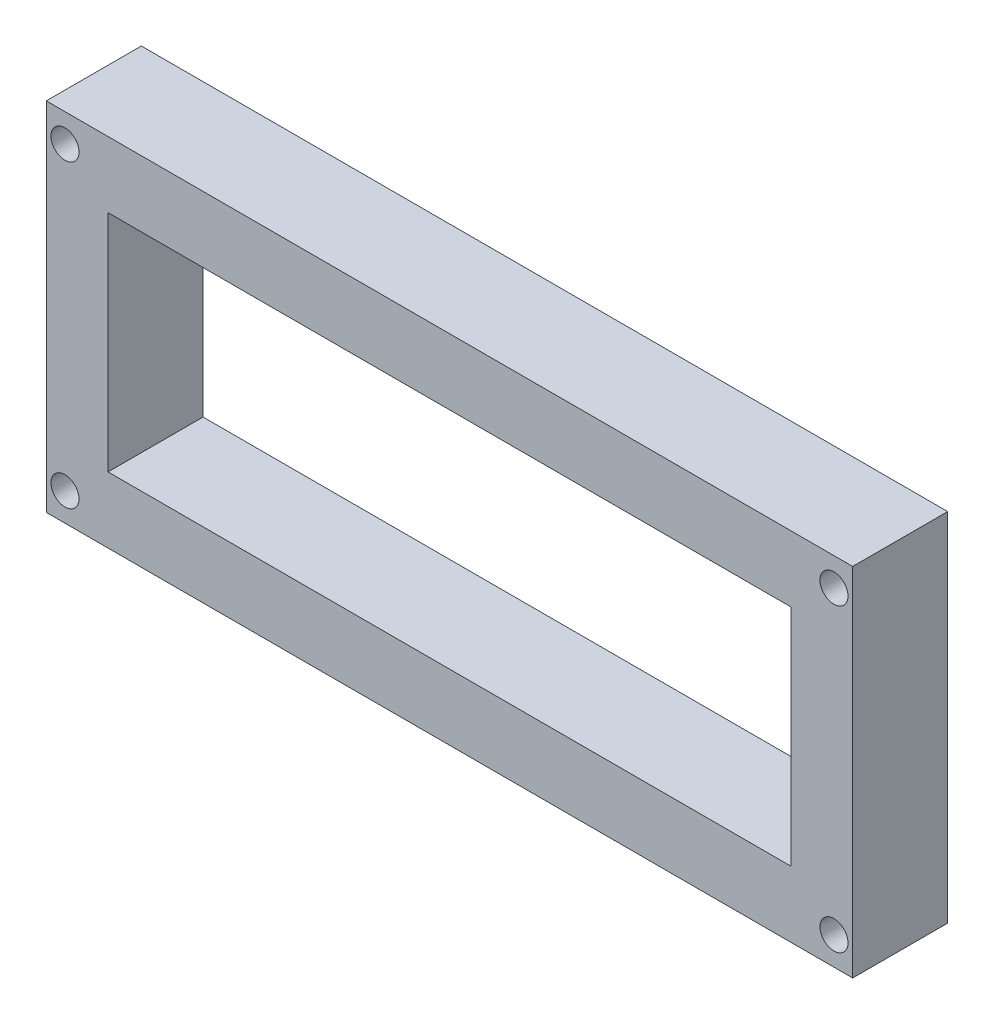
SolidWorks part; units mm, degrees
ref_plane "Front Plane" through (0, 0, 0) normal (0, 0, 1) x (1, 0, 0)
ref_plane "Top Plane" through (0, 0, 0) normal (0, 1, 0) x (1, 0, 0)
ref_plane "Right Plane" through (0, 0, 0) normal (1, 0, 0) x (0, 0, -1)
sketch "Sketch1" plane through (0, 0, 0) normal (0, 0, 1) x (1, 0, 0)
  line L1 (-43.1, 19.05) -> (43.1, 19.05)
  line L2 (-43.1, 19.05) -> (-43.1, -19.05)
  line L3 (-43.1, -19.05) -> (43.1, -19.05)
  line L4 (43.1, 19.05) -> (43.1, -19.05)
  line L5 (-36.5, 12) -> (36.5, 12)
  line L6 (-36.5, 12) -> (-36.5, -12)
  line L7 (-36.5, -12) -> (36.5, -12)
  line L8 (36.5, 12) -> (36.5, -12)
  point P4 (0, 19.05)
  point P5 (-43.1, 0)
  point P11 (0, 12)
  point P12 (-36.5, 0)
  dimension "D1" = 86.2
  dimension "D2" = 38.1
  dimension "D3" = 73
  dimension "D4" = 24
extrude "Boss-Extrude1" add sketch "Sketch1" along normal blind 10.16
sketch "Sketch2" plane through (0, 0, 10.16) normal (0, 0, 1) x (1, 0, 0)
  line L0 (43.1, -19.05) -> (43.1, 19.05) construction
  line L1 (43.1, 19.05) -> (-43.1, 19.05) construction
  line L2 (0, -5.588) -> (0, 5.588) construction
  line L4 (5.588, 0) -> (-5.588, 0) construction
  circle A1 centre (41.1, 16.05) radius 1.5
  circle A2 centre (-41.1, 16.05) radius 1.5
  circle A3 centre (-41.1, -16.05) radius 1.5
  circle A4 centre (41.1, -16.05) radius 1.5
  dimension "D1" = 2
  dimension "D3" = 3
  dimension "D2" = 3
extrude "Cut-Extrude1" cut sketch "Sketch2" against normal blind 10.16
